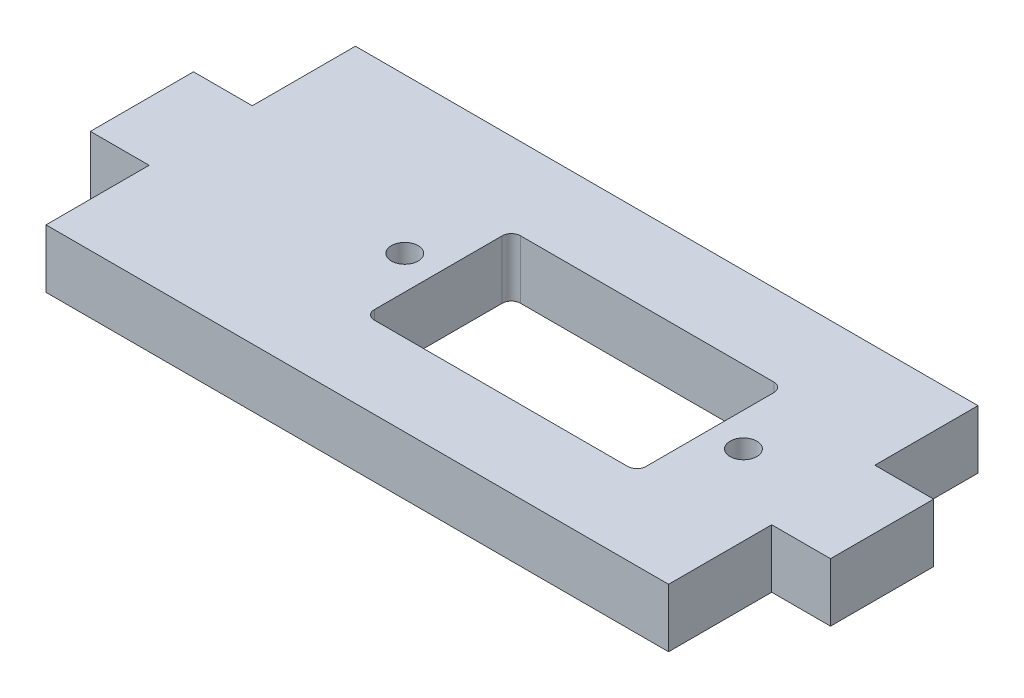
SolidWorks part; units mm, degrees
ref_plane "Front Plane" through (0, 0, 0) normal (0, 0, 1) x (1, 0, 0)
ref_plane "Top Plane" through (0, 0, 0) normal (0, 1, 0) x (1, 0, 0)
ref_plane "Right Plane" through (0, 0, 0) normal (1, 0, 0) x (0, 0, -1)
sketch "Sketch1" plane through (0, 0, 0) normal (0, 1, 0) x (1, 0, 0)
  line L1 (0, 0) -> (101.6, 0)
  line L2 (0, 0) -> (0, 25.4)
  line L3 (0, 25.4) -> (101.6, 25.4)
  line L4 (101.6, 0) -> (101.6, 25.4)
  line L5 (0, 0) -> (101.6, 25.4) construction
  line L6 (0, 25.4) -> (101.6, 0) construction
  point P4 (50.8, 12.7)
  dimension "D1" = 101.6
  dimension "D2" = 25.4
extrude "Boss-Extrude1" add sketch "Sketch1" along normal blind 4.8
sketch "Sketch2" plane through (0, 4.8, 0) normal (0, 1, 0) x (1, 0, 0)
  arc A2 (43.4974, 12.15) -> (43.4974, 13.25) centre (44.45, 12.7) ccw construction
  arc A3 (73.2026, 13.25) -> (73.2026, 12.15) centre (72.25, 12.7) ccw construction
  circle A5 centre (72.25, 12.7) radius 1.1
  circle A6 centre (44.45, 12.7) radius 1.1
extrude "Cut-Extrude1" cut sketch "Sketch2" against normal through all
sketch "Sketch3" plane through (0, 0, 0) normal (0, -1, 0) x (1, 0, 0)
  line L20 (69.5, -17.95) -> (69.5, -7.45)
  line L21 (68.75, -6.7) -> (47.95, -6.7)
  line L22 (47.2, -7.45) -> (47.2, -17.95)
  line L23 (47.95, -18.7) -> (68.75, -18.7)
  line L24 (22.8718, 0) -> (22.8718, -8.4667)
  line L25 (22.8718, -8.4667) -> (27.6978, -8.4667)
  line L26 (27.6978, -8.4667) -> (27.6978, 0)
  line L27 (27.6978, 0) -> (22.8718, 0)
  line L28 (78.8042, 0) -> (78.8042, -8.4667)
  line L29 (78.8042, -8.4667) -> (83.6302, -8.4667)
  line L30 (83.6302, -8.4667) -> (83.6302, 0)
  line L31 (83.6302, 0) -> (78.8042, 0)
  line L32 (27.6978, -25.4) -> (27.6978, -16.9333)
  line L33 (27.6978, -16.9333) -> (22.8718, -16.9333)
  line L34 (22.8718, -16.9333) -> (22.8718, -25.4)
  line L35 (22.8718, -25.4) -> (27.6978, -25.4)
  line L36 (83.6302, -25.4) -> (83.6302, -16.9333)
  line L37 (83.6302, -16.9333) -> (78.8042, -16.9333)
  line L38 (78.8042, -16.9333) -> (78.8042, -25.4)
  line L39 (78.8042, -25.4) -> (83.6302, -25.4)
  arc A4 (69.5, -7.45) -> (68.75, -6.7) centre (68.75, -7.45) ccw
  arc A5 (47.95, -6.7) -> (47.2, -7.45) centre (47.95, -7.45) ccw
  arc A6 (47.2, -17.95) -> (47.95, -18.7) centre (47.95, -17.95) ccw
  arc A7 (68.75, -18.7) -> (69.5, -17.95) centre (68.75, -17.95) ccw
extrude "Cut-Extrude2" cut sketch "Sketch3" against normal through all
sketch "Sketch4" plane through (0, 0, 0) normal (0, -1, 0) x (1, 0, 0)
  line L0 (101.6, 0) -> (101.6, -25.4) construction
  line L1 (101.6, 0) -> (83.6302, 0)
  line L2 (101.6, 0) -> (101.6, -25.4)
  line L3 (101.6, -25.4) -> (83.6302, -25.4)
  line L4 (83.6302, 0) -> (83.6302, -25.4)
  line L5 (101.6, 0) -> (83.6302, -25.4) construction
  line L6 (101.6, -25.4) -> (83.6302, 0) construction
  line L7 (22.8718, -25.4) -> (0, -25.4) construction
  line L8 (0, 0) -> (22.8718, 0)
  line L9 (0, 0) -> (0, -25.4)
  line L10 (0, -25.4) -> (22.8718, -25.4)
  line L11 (22.8718, 0) -> (22.8718, -25.4)
  line L12 (0, 0) -> (22.8718, -25.4) construction
  line L13 (0, -25.4) -> (22.8718, 0) construction
  line L14 (22.8718, -16.9333) -> (22.8718, -25.4) construction
  point P4 (92.6151, -12.7)
  point P12 (11.4359, -12.7)
extrude "Cut-Extrude3" cut sketch "Sketch4" against normal through all
equation "\"MDF\"= 4.8mm"
equation "\"Foamcore\"= 4.6mm"
equation "\"GMaterial\"= \"MDF\""
equation "\"PCB\" = 1.6mm"
equation "\"BaseWidth\" = 10in"
equation "\"SkidLength\" = 1in"
equation "\"SkidClearance\" = 0.4in"
equation "\"MotorMountLength\" = 2in"
equation "\"MotorMountWidth\" = \"GMaterial\""
equation "\"MotorMountHeight\" = 2.25in"
equation "\"UnoStackWidth\" = 77.4mm"
equation "\"UnoStackLength\" = 79.8mm"
equation "\"UnoStackHeight\" = 34.2mm"
equation "\"TallHexRiserHeight\" = 22.2mm"
equation "\"PingPongBallSize\" = 40mm"
equation "\"BarrelLength\" = 9in"
equation "\"BarrelSize\" = \"PingPongBallSize\""
equation "\"PlatformLength\" = 4in"
equation "\"PlatformWidth\" = 6in"
equation "\"WheelDiameter\"=2.99213"
equation "\"ServoMountHeight\"=2.49223"
equation "\"ServoGearHeight\" = 0.95330261in"
equation "\"ServoMountLength\"= 1.53774"
equation "\"PivotHoleRadius\"= 0.616358"
equation "\"PlatformMountHeight\" = 3.19"
equation "\"TensionOffSet\"= .3mm"
equation "\"MotorMountWedge\"=0.333333"
equation "\"LaserCutterOffset\"= .3mm"
equation "\"BumperWidth\"=11"
equation "\"PitcherWheelCompression\" = 2.5mm"
equation "\"PitchingWheelWidth\" = 26.2mm"
equation "\"PitchingWheelDiameter\" = 65.5mm"
equation "\"PitchingWheelMountOffset\" = 8.4mm"
equation "\"PitchingWheelInnerDiameter\" = 45.5mm"
equation "\"PitchingWheelBoltShoulder\" = 4.5mm"
equation "\"BrassCouplingLength\" = 18mm"
equation "\"PitchingMotorHeight\" = 57.0mm"
equation "\"PitchingMotorShaftTopHeight\" = \"PitchingMotorHeight\" - 44.1mm"
equation "\"PitchingMotorBodyHeight\" = 38mm"
equation "\"PitchingMotorTopShoulderHeight\" = 40.6mm - \"PitchingMotorBodyHeight\" "
equation "\"PitchingMotorBottomShoulderHeight\" = 40.2mm - \"PitchingMotorBodyHeight\""
equation "\"PitchingMotorBottomShaftHeight\" = \"PitchingMotorHeight\" - \"PitchingMotorShaftTopHeight\" - \"PitchingMotorTopShoulderHeight\" - \"PitchingMotorBodyHeight\" - \"PitchingMotorBottomShoulderHeight\""
equation "\"PitchingMotorShaftDiameter\" = 2.2mm"
equation "\"PitchingMotorBodyDiameter\" = 27.4mm"
equation "\"PitchingMotorTopShoulderDiameter\" = 9.8mm"
equation "\"PitchingMotorBottomShoulderDiameter\" = 9.8mm"
equation "\"BrassCouplingHexSize\" = 12mm"
equation "\"BrassCouplingBoreSize\" = 3.17mm"
equation "\"PitchingMotorMountingHoleDistance\" = 16mm"
equation "\"Acrylic\" = 4.4mm"
equation "\"PitchingMotorDistance\" = \"PitchingWheelDiameter\" + \"PingPongBallSize\" - \"PitcherWheelCompression\"*2"
equation "\"PitchingMotorPlatformOffset\"=1"
equation "\"ServoPlatformOffset\"=1.64173"
equation "\"BallBearingDiameter\" = 22mm"
equation "\"BallBearingWidth\" = 9mm"
equation "\"BallBearingHexShoulder\" = 9mm - 5.9mm"
equation "\"BallBearingHexSize\" = .36in"
equation "\"PlatformMountFootLength\"=0.857143"
equation "\"WheelWidth\"= 26mm"
equation "\"ServoMountReductionBackHeight\"=2.25"
equation "\"PlatformBottomWidthThird\" =  0.857143in"
equation "\"PlatformMountBackReductionHeight\"= 2.5in"
equation "\"PlatformMountBackReductionWidth\"= 3/7in"
equation "\"PlatformMountFrontReductionWidth\" =  1.46226in"
equation "\"PlatformMountFrontReductionHeight\" = 2.5in"
equation "\"D1@Boss-Extrude1\"=\"MDF\""
